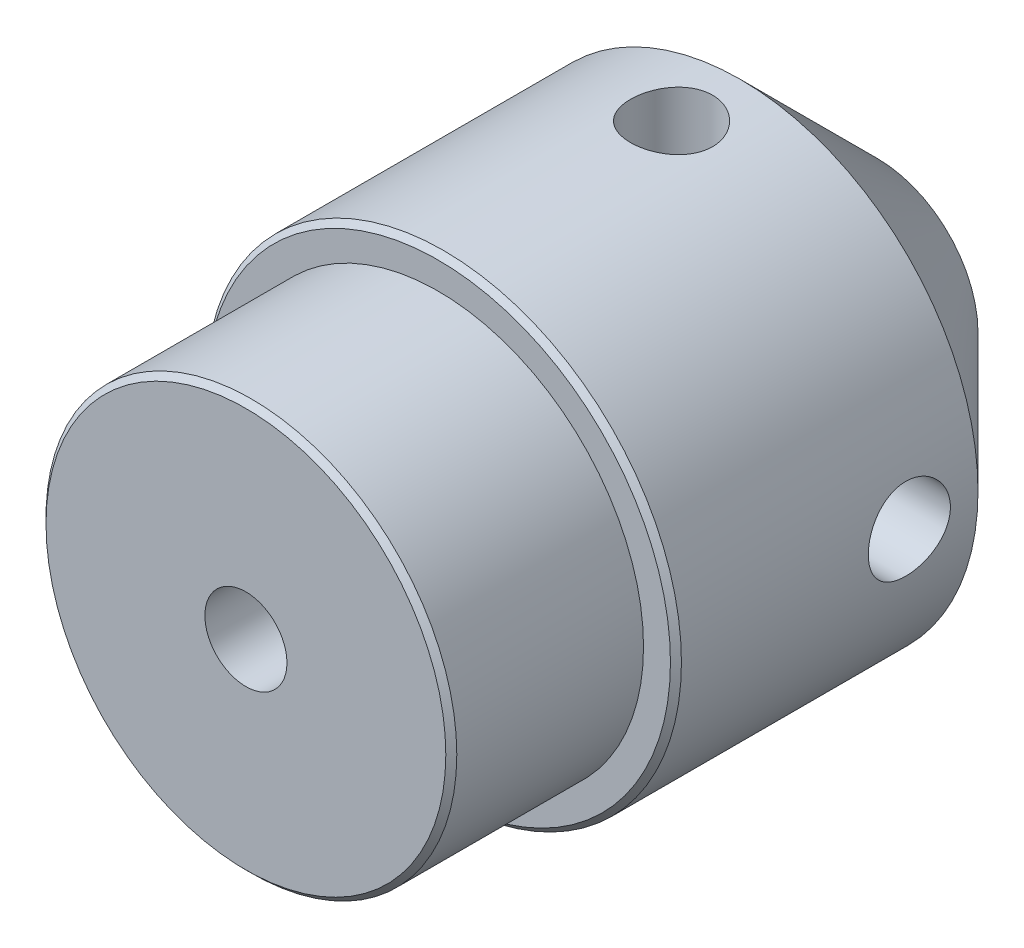
SolidWorks part; units mm, degrees
material "6061-T6 (SS)"
ref_plane "Front Plane" through (0, 0, 0) normal (0, 0, 1) x (1, 0, 0)
ref_plane "Top Plane" through (0, 0, 0) normal (0, 1, 0) x (1, 0, 0)
ref_plane "Right Plane" through (0, 0, 0) normal (1, 0, 0) x (0, 0, -1)
sketch "Sketch1" plane through (0, 0, 0) normal (0, 0, 1) x (1, 0, 0)
  circle A2 centre (0, 0) radius 11
  dimension "D1" = 22
extrude "Boss-Extrude1" add sketch "Sketch1" along normal blind 20.32
sketch "Sketch2" plane through (0, 0, 0) normal (0, 1, 0) x (1, 0, 0)
  line L0 (0, 0) -> (0, -3.5) construction
  line L1 (0, -3.5) -> (0, -15.5) construction
  line L2 (0, -15.5) -> (0, -20.32) construction
  line L3 (-11, -20.32) -> (11, -20.32) construction
  line L4 (11, 0) -> (-11, 0) construction
  circle A0 centre (0, -9.525) radius 1.9939
  dimension "D2" = 3.9878
  dimension "D5" = 9.525
  dimension "D1" = 15.5
  dimension "D3" = 12
  dimension "D4" = 4.82
sketch "Sketch5" plane through (0, 0, 20.32) normal (0, 0, 1) x (1, 0, 0)
  circle A0 centre (0, 0) radius 9.5
  dimension "D1" = 19
extrude "Boss-Extrude6" add sketch "Sketch5" along normal blind 8.89
hole_wizard "B (0.238) Diameter Hole1" positions "Sketch8" profile "Sketch7" hole size "B" standard "ANSI Inch"
sketch "Sketch8" plane through (0, 0, 0) normal (0, 0, -1) x (-1, 0, 0)
  point P2 (0, 0)
sketch "Sketch7" plane through (0, 0, 0) normal (1, 0, 0) x (0, 1, 0)
  line L0 (0, 0) -> (0, 20.8662)
  line L1 (0, 20.8662) -> (3.0226, 19.05)
  line L2 (3.0226, 19.05) -> (3.0226, 0)
  line L5 (3.0226, 0) -> (0, 0)
  line L10 (0, 20.8662) -> (-3.0226, 19.05) construction
  line L11 (0, -6.35) -> (0, 107.95) construction
  dimension "Hole Dia." = 6.0452
  dimension "Hole Depth" = 19.05
  dimension "Drill Angle" = 118
hole_wizard "#10-24 Tapped Hole1" positions "3DSketch1" profile "Sketch6" tap size "#10-24" standard "ANSI Inch"
sketch3d "3DSketch1"
  point P0 (0, 11, 9.525)
sketch "Sketch6" plane through (0, 11, 9.525) normal (1, 0, 0) x (0, 0, 1)
  line L0 (0, 0) -> (0, 22)
  line L1 (0, 22) -> (1.8986, 22)
  line L2 (1.8986, 22) -> (1.8986, 0)
  line L5 (1.8986, 0) -> (0, 0)
  line L11 (0, -6.35) -> (0, 107.95) construction
  dimension "Thread Major Dia." = 3.7973
  dimension "Thru Tap Drill Depth" = 22
hole_wizard "#10-24 Tapped Hole2" positions "Sketch10" profile "Sketch9" tap size "#10-24" standard "ANSI Inch" end condition up to next
sketch "Sketch10" plane through (0, 0, 29.21) normal (0, 0, 1) x (1, 0, 0)
  point P0 (0, 0)
sketch "Sketch9" plane through (0, 0, 29.21) normal (1, 0, 0) x (0, -1, 0)
  line L0 (0, 0) -> (0, 8.3438)
  line L1 (0, 8.3438) -> (1.8986, 8.3438)
  line L2 (1.8986, 8.3438) -> (1.8986, 0)
  line L5 (1.8986, 0) -> (0, 0)
  line L11 (0, -6.35) -> (0, 107.95) construction
  dimension "Thru Tap Drill Dia." = 3.7973
  dimension "Thru Tap Drill Depth" = 8.3438
cosmetic thread "Hole Thread1" parameters "D2"=4.826
chamfer "Chamfer1" distance 6.35 angle 45 1 edges at (11, 0, 0)
chamfer "Chamfer2" distance 0.254 angle 45 2 edges at (11, 0, 20.32) (9.5, 0, 29.21)
pattern_circular "CirPattern1" count 2 every 90 about axis through (0, 0, 20.32) along (0, 0, -1) of "#10-24 Tapped Hole1"
